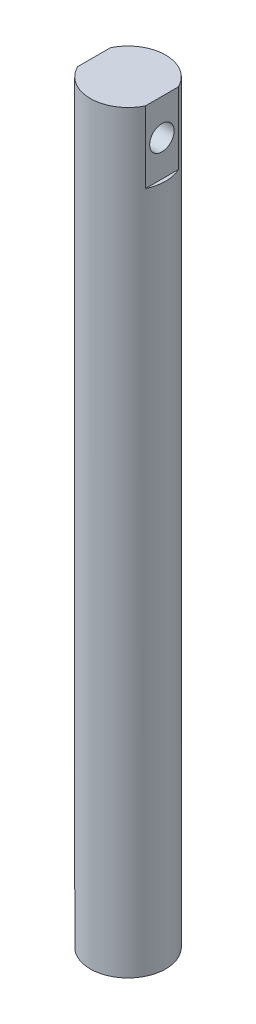
SolidWorks part; units mm, degrees
ref_plane "前视基准面" through (0, 0, 0) normal (0, 0, 1) x (1, 0, 0)
ref_plane "上视基准面" through (0, 0, 0) normal (0, 1, 0) x (1, 0, 0)
ref_plane "右视基准面" through (0, 0, 0) normal (1, 0, 0) x (0, 0, -1)
sketch "草图1" plane through (0, 0, 0) normal (0, 1, 0) x (1, 0, 0)
  circle A0 centre (0, 0) radius 10
  dimension "D1" = 20
extrude "凸台-拉伸1" add sketch "草图1" along normal blind 200
sketch "草图2" plane through (0, 200, 0) normal (0, 1, 0) x (1, 0, 0)
  line L1 (-9, 4.3589) -> (9, 4.3589)
  line L2 (-9, 4.3589) -> (-9, -4.3589)
  line L3 (-9, -4.3589) -> (9, -4.3589)
  line L4 (9, 4.3589) -> (9, -4.3589)
  circle A0 centre (0, 0) radius 10 construction
  arc A1 (-9, 4.3589) -> (-9, -4.3589) centre (0, 0) ccw
  arc A2 (9, 4.3589) -> (9, -4.3589) centre (0, 0) cw
  circle M3 centre (0, 0) radius 10
  dimension "D1" = 18
extrude "切除-拉伸1" cut sketch "草图2" against normal blind 19 contours L2 M3 | L4 M3
sketch "草图3" plane through (-9, 0, 0) normal (-1, 0, 0) x (0, 0, 1)
  line L0 (-4.3589, 200) -> (4.3589, 200) construction
  circle A0 centre (0, 190.5) radius 3.25
  dimension "D1" = 6.5
  dimension "D2" = 9.5
extrude "切除-拉伸4" cut sketch "草图3" against normal through all
